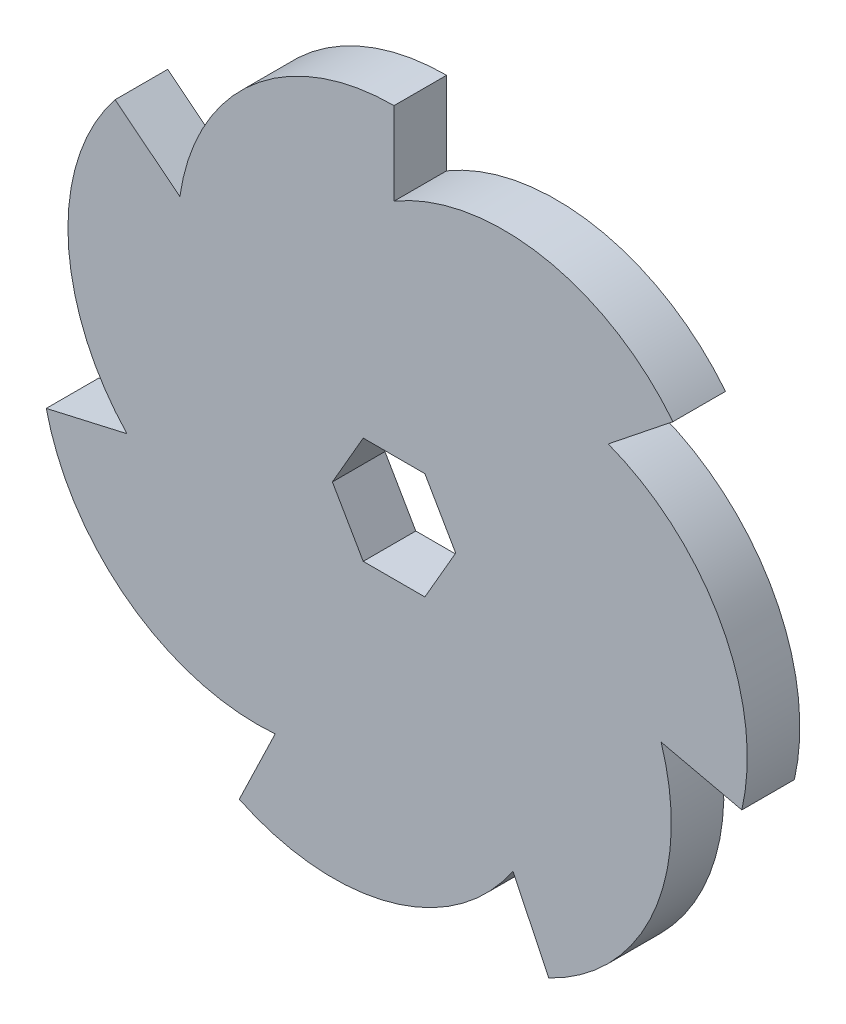
SolidWorks part; units mm, degrees
ref_plane "Front Plane" through (0, 0, 0) normal (0, 0, 1) x (1, 0, 0)
ref_plane "Top Plane" through (0, 0, 0) normal (0, 1, 0) x (1, 0, 0)
ref_plane "Right Plane" through (0, 0, 0) normal (1, 0, 0) x (0, 0, -1)
sketch "Sketch1" plane through (0, 0, 0) normal (0, 0, 1) x (1, 0, 0)
  line L0 (0, 0) -> (0, 33.1)
  line L2 (0, 0) -> (33.6969, 26.8724)
  line L4 (33.1, 0) -> (38.1, 0) construction
  line L5 (38.1, 0) -> (43.1, 0) construction
  circle A0 centre (0, 0) radius 38.1 construction
  circle A1 centre (0, 0) radius 33.1 construction
  circle A2 centre (0, 0) radius 43.1 construction
  arc A6 (0, 33.1) -> (33.6969, 26.8724) centre (13.2611, 10.5754) cw
  dimension "D1" = 76.2
  dimension "D4" = 51.429
  dimension "D2" = 10
extrude "Boss-Extrude1" add sketch "Sketch1" along normal mid plane 6.35
pattern_circular "CirPattern1" count 7 over 360 about axis through (0, 0, 0) along (0, 0, 1) of "Boss-Extrude1"
sketch "Sketch2" plane through (0, 0, 3.175) normal (0, 0, 1) x (1, 0, 0)
  line L1 (7.4478, 0) -> (3.7239, 6.45)
  line L2 (3.7239, 6.45) -> (-3.7239, 6.45)
  line L3 (-3.7239, 6.45) -> (-7.4478, 0)
  line L4 (-7.4478, 0) -> (-3.7239, -6.45)
  line L5 (-3.7239, -6.45) -> (3.7239, -6.45)
  line L6 (3.7239, -6.45) -> (7.4478, 0)
  circle A0 centre (0, 0) radius 6.45 construction
  dimension "D1" = 12.9
extrude "Cut-Extrude1" cut sketch "Sketch2" against normal through all
equation "\"D\"= 76.2mm'Pitch Diameter"
equation "\"D1@Sketch1\"=\"D\""
equation "\"B\"= 10mm'Blade Radius"
equation "\"N\"= 7'Number of Blades"
equation "\"D4@Sketch1\"=360deg / \"N\""
equation "\"D1@CirPattern1\"=\"N\""
equation "\"D2@Sketch1\"=\"B\""
equation "\"H\"= 12.9mm'Hex Shaft Diameter"
equation "\"D1@Sketch2\"=\"H\""
